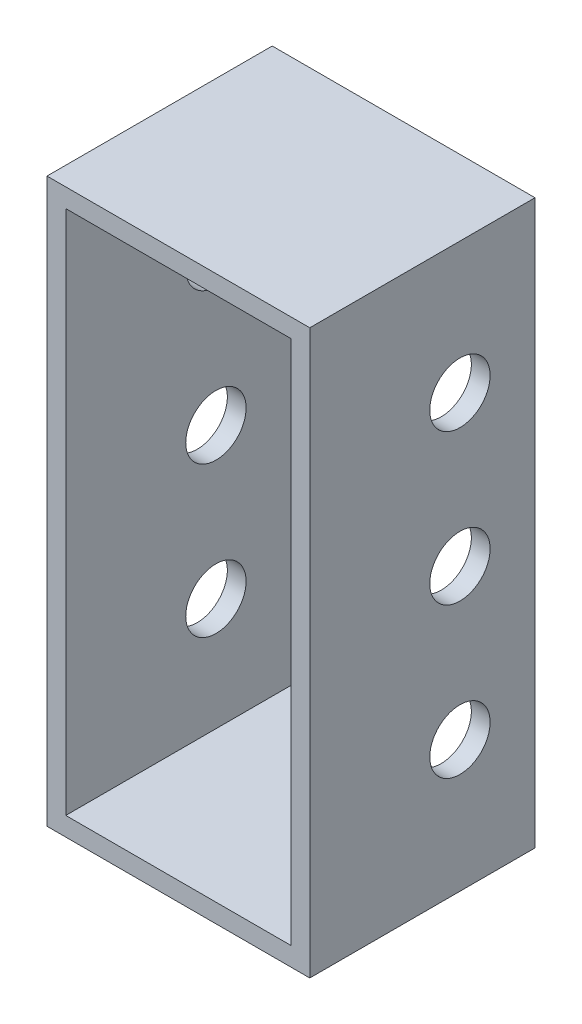
SolidWorks part; units mm, degrees
material "Nylon 101"
ref_plane "Front Plane" through (0, 0, 0) normal (0, 0, 1) x (1, 0, 0)
ref_plane "Top Plane" through (0, 0, 0) normal (0, 1, 0) x (1, 0, 0)
ref_plane "Right Plane" through (0, 0, 0) normal (1, 0, 0) x (0, 0, -1)
sketch "Sketch1" plane through (0, 0, 0) normal (0, 1, 0) x (1, 0, 0)
  line L1 (0, 0) -> (22.225, 0)
  line L2 (0, 0) -> (0, 19.05)
  line L3 (0, 19.05) -> (22.225, 19.05)
  line L4 (22.225, 0) -> (22.225, 19.05)
  dimension "D1" = 22.225
  dimension "D2" = 19.05
extrude "Boss-Extrude1" add sketch "Sketch1" along normal mid plane 47.625
sketch "Sketch2" plane through (0, 0, 0) normal (-1, 0, 0) x (0, 0, 1)
  line L0 (-12.7, -23.8125) -> (-12.7, 23.8125) construction
  line L1 (-19.05, -23.8125) -> (0, -23.8125) construction
  line L2 (-19.05, 23.8125) -> (0, 23.8125) construction
  line L3 (0, 23.8125) -> (0, -23.8125) construction
  circle A0 centre (-12.7, 12.7) radius 2.5527
  circle A1 centre (-12.7, -12.7) radius 2.5527
  circle A2 centre (-12.7, 0) radius 2.5527
  dimension "D2" = 5.1054
  dimension "D1" = 12.7
  dimension "D3" = 11.1125
  dimension "D4" = 12.7
  dimension "D5" = 12.7
extrude "Cut-Extrude1" cut sketch "Sketch2" against normal through all
shell "Shell1" thickness 1.5875
